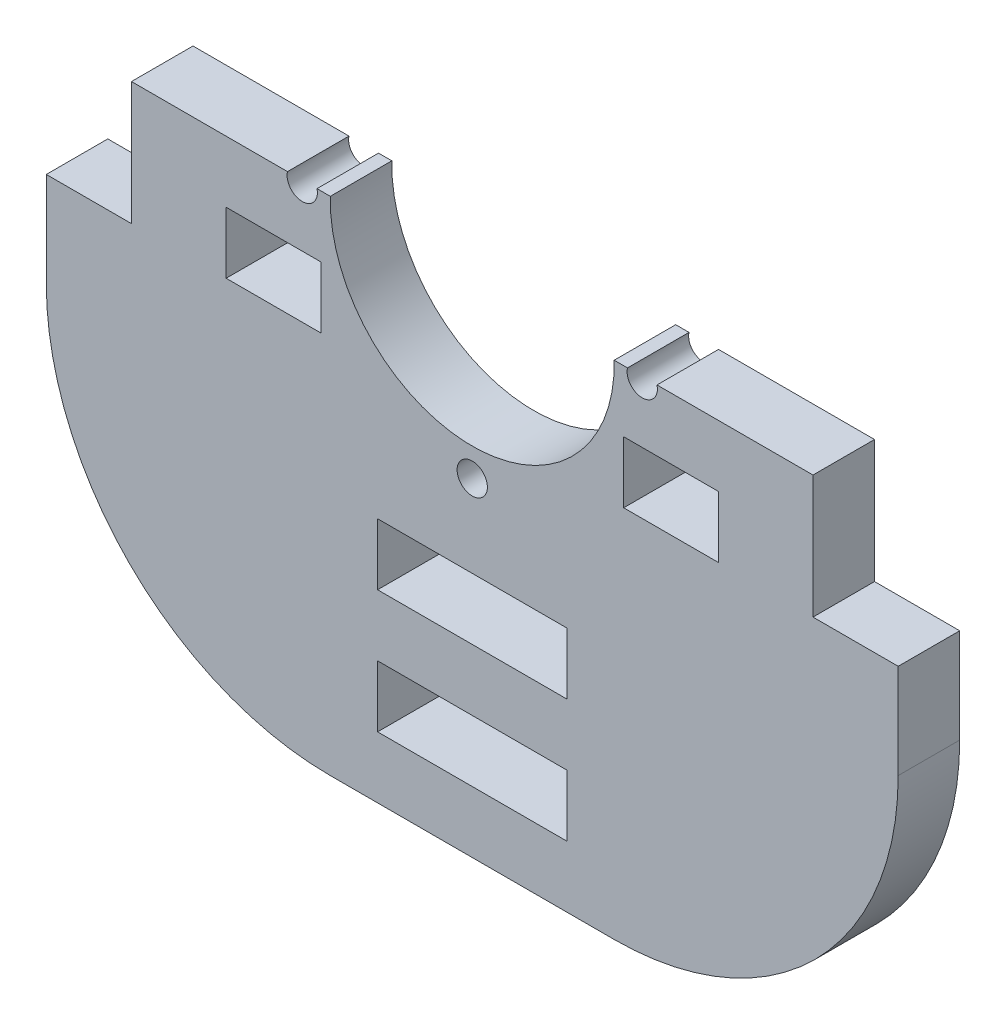
SolidWorks part; units mm, degrees
ref_plane "Front Plane" through (0, 0, 0) normal (0, 0, 1) x (1, 0, 0)
ref_plane "Top Plane" through (0, 0, 0) normal (0, 1, 0) x (1, 0, 0)
ref_plane "Right Plane" through (0, 0, 0) normal (1, 0, 0) x (0, 0, -1)
sketch "Sketch1" plane through (0, 0, 0) normal (0, 0, 1) x (1, 0, 0)
  line L1 (0, 0) -> (90, 0)
  line L2 (0, 0) -> (0, 40)
  line L3 (0, 40) -> (90, 40)
  line L4 (90, 0) -> (90, 40)
  line L5 (9, 53) -> (81, 53)
  line L6 (9, 53) -> (9, 40)
  line L7 (9, 40) -> (81, 40)
  line L8 (81, 53) -> (81, 40)
  dimension "D1" = 90
  dimension "D2" = 40
  dimension "D3" = 13
  dimension "D4" = 72
  dimension "D5" = 9
extrude "Boss-Extrude1" add sketch "Sketch1" along normal blind 6.5 contours L8 L5 L6 L3 | L1 L4 L3 L2
fillet "Fillet2" radius 30 2 edges at (90, 0, 3.25) (0, 0, 3.25)
sketch "Sketch2" plane through (0, 0, 6.5) normal (0, 0, 1) x (1, 0, 0)
  line L0 (9, 53) -> (9, 40) construction
  line L1 (45, 70.5998) -> (62.9605, 52.6393) construction
  line L2 (45, 70.5998) -> (27.0395, 52.6393) construction
  line L3 (27.0395, 52.6393) -> (45, 34.6788) construction
  line L4 (62.9605, 52.6393) -> (45, 34.6788) construction
  line L5 (45, 70.5998) -> (45, 34.6788) construction
  line L6 (27.0395, 52.6393) -> (62.9605, 52.6393) construction
  circle A2 centre (45, 52.6393) radius 15
  circle A4 centre (62.9605, 52.6393) radius 1.6
  circle A5 centre (45, 34.6788) radius 1.6
  circle A6 centre (27.0395, 52.6393) radius 1.6
  dimension "D1" = 3.2
  dimension "D2" = 3.2
  dimension "D3" = 3.2
  dimension "D9" = 0
  dimension "D13" = 30
  dimension "D4" = 25.4
  dimension "D5" = 25.4
  dimension "D6" = 0
  dimension "D7" = 0
  dimension "D8" = 0
  dimension "D10" = 0
  dimension "D11" = 0
  dimension "D12" = 36
extrude "motor clearance" cut sketch "Sketch2" against normal through all
sketch "Sketch3" plane through (0, 0, 6.5) normal (0, 0, 1) x (1, 0, 0)
  line L1 (19, 40) -> (29, 40)
  line L2 (19, 40) -> (19, 46.5)
  line L3 (19, 46.5) -> (29, 46.5)
  line L4 (29, 40) -> (29, 46.5)
  line L5 (71, 40) -> (61, 40)
  line L6 (71, 40) -> (71, 46.5)
  line L7 (71, 46.5) -> (61, 46.5)
  line L8 (61, 40) -> (61, 46.5)
  dimension "D1" = 6.5
  dimension "D2" = 6.5
  dimension "D3" = 10
  dimension "D4" = 10
  dimension "D5" = 10
  dimension "D6" = 10
extrude "cut side wheel holes" cut sketch "Sketch3" against normal up to next
sketch "Sketch5" plane through (0, 0, 6.5) normal (0, 0, 1) x (1, 0, 0)
  line L0 (45, 0) -> (45, 6.5) construction
  line L2 (35, 19.5) -> (55, 19.5)
  line L3 (35, 19.5) -> (35, 26)
  line L4 (35, 26) -> (55, 26)
  line L5 (55, 19.5) -> (55, 26)
  line L6 (35, 6.5) -> (55, 6.5)
  line L7 (35, 6.5) -> (35, 13)
  line L8 (35, 13) -> (55, 13)
  line L10 (55, 6.5) -> (55, 13)
  line L11 (30, 0) -> (60, 0) construction
  line L12 (45, 19.5) -> (45, 13) construction
  dimension "D1" = 6.5
  dimension "D2" = 6.5
  dimension "D3" = 6.5
  dimension "D4" = 6.5
  dimension "D5" = 20
extrude "Cut-Extrude1" cut sketch "Sketch5" against normal up to next
